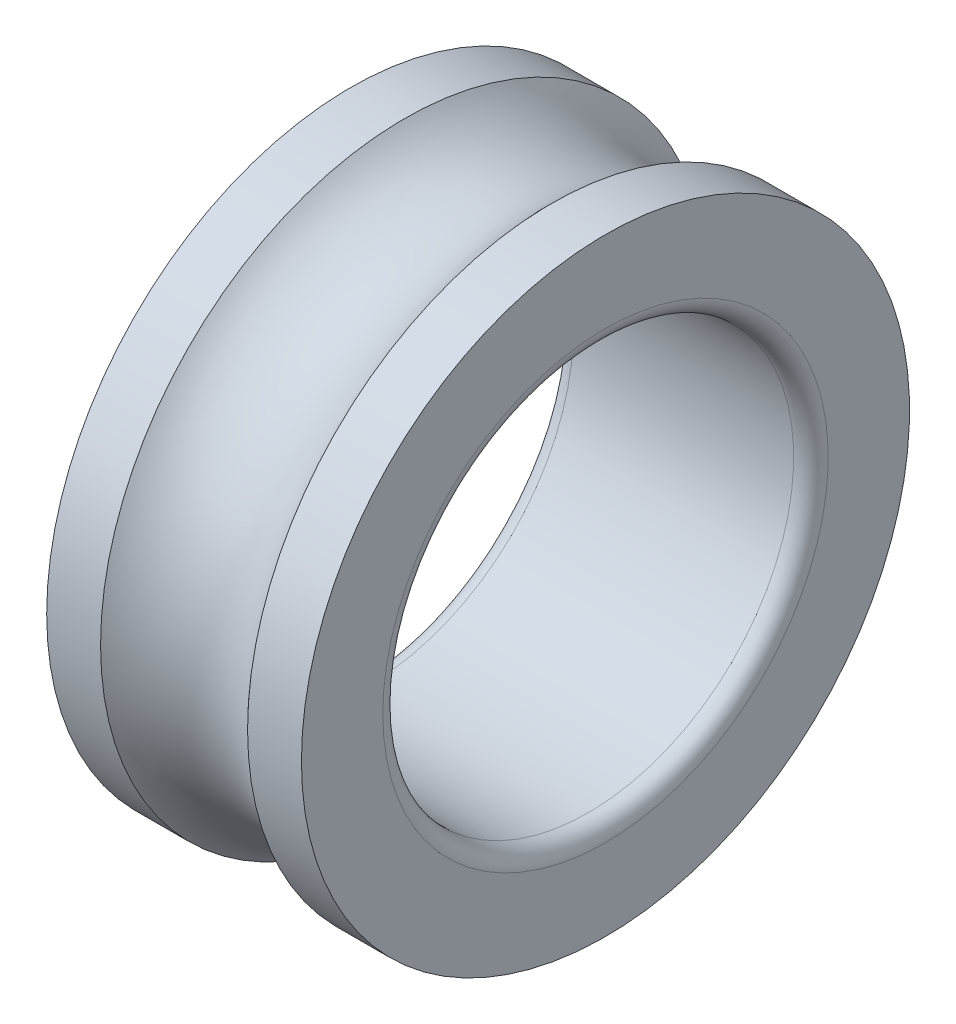
SolidWorks part; units mm, degrees
ref_plane "Спереди" through (0, 0, 0) normal (0, 0, 1) x (1, 0, 0)
ref_plane "Сверху" through (0, 0, 0) normal (0, 1, 0) x (1, 0, 0)
ref_plane "Справа" through (0, 0, 0) normal (1, 0, 0) x (0, 0, -1)
sketch "Sketch1" plane through (0, 0, 0) normal (0, 0, 1) x (1, 0, 0)
  line L0 (-20.9591, 0) -> (36.2642, 0) construction
  line L1 (0, 25) -> (0, 0) construction
  line L2 (13.4, 25) -> (-13.4, 25)
  line L3 (15.5, 27.1) -> (15.5, 37)
  line L4 (15.5, 37) -> (8.9443, 37)
  line L5 (-15.5, 27.1) -> (-15.5, 37)
  line L6 (15.5, 25) -> (-15.5, 37) construction
  line L7 (15.5, 37) -> (-15.5, 25) construction
  line L8 (-8.9443, 37) -> (-15.5, 37)
  arc A0 (-8.9443, 37) -> (8.9443, 37) centre (0, 45) ccw
  arc A1 (13.4, 25) -> (15.5, 27.1) centre (13.4, 27.1) ccw
  arc A2 (-13.4, 25) -> (-15.5, 27.1) centre (-13.4, 27.1) cw
  point P3 (0, 31)
  dimension "D5" = 12
  dimension "D6" = 2.1
  dimension "D1" = 31
  dimension "D2" = 25
  dimension "D3" = 37
  dimension "D4" = 8
revolve "Revolve1" add sketch "Sketch1" angle 360 about L0
